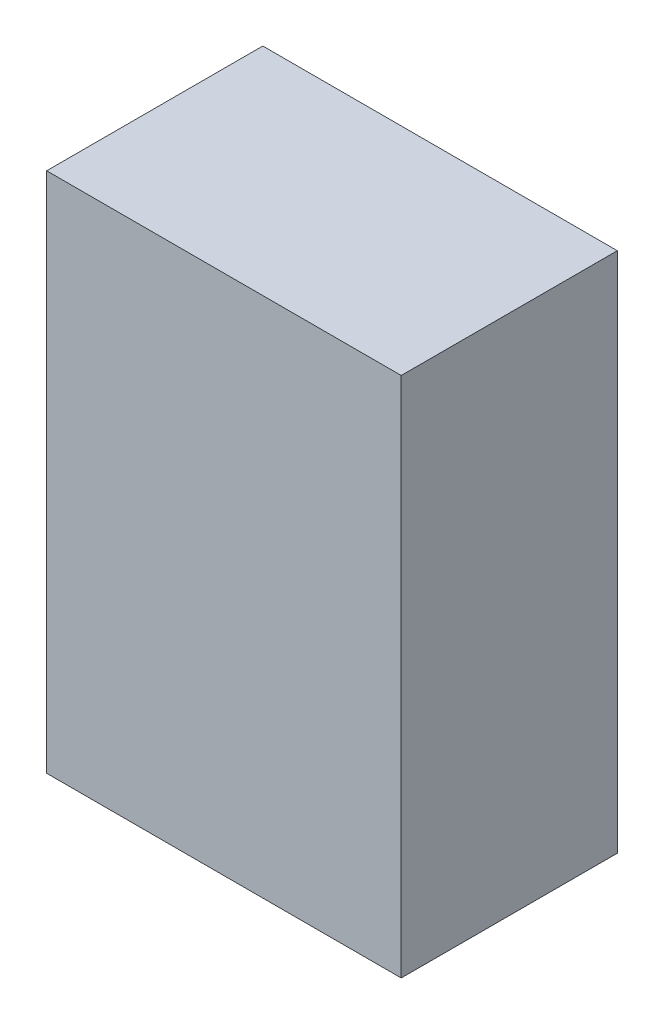
SolidWorks part; units mm, degrees
ref_plane "Front Plane" through (0, 0, 0) normal (0, 0, 1) x (1, 0, 0)
ref_plane "Top Plane" through (0, 0, 0) normal (0, 1, 0) x (1, 0, 0)
ref_plane "Right Plane" through (0, 0, 0) normal (1, 0, 0) x (0, 0, -1)
sketch "Sketch1" plane through (0, 0, 0) normal (0, 0, 1) x (1, 0, 0)
  line L0 (-74.0908, 55.3292) -> (-74.0908, -65.3891)
  line L1 (-74.0908, 55.3292) -> (7.9357, 55.3292)
  line L2 (7.9357, 55.3292) -> (7.9357, -65.3891)
  line L3 (-74.0908, -65.3891) -> (7.9357, -65.3891)
extrude "Boss-Extrude2" add sketch "Sketch1" along normal blind 50
